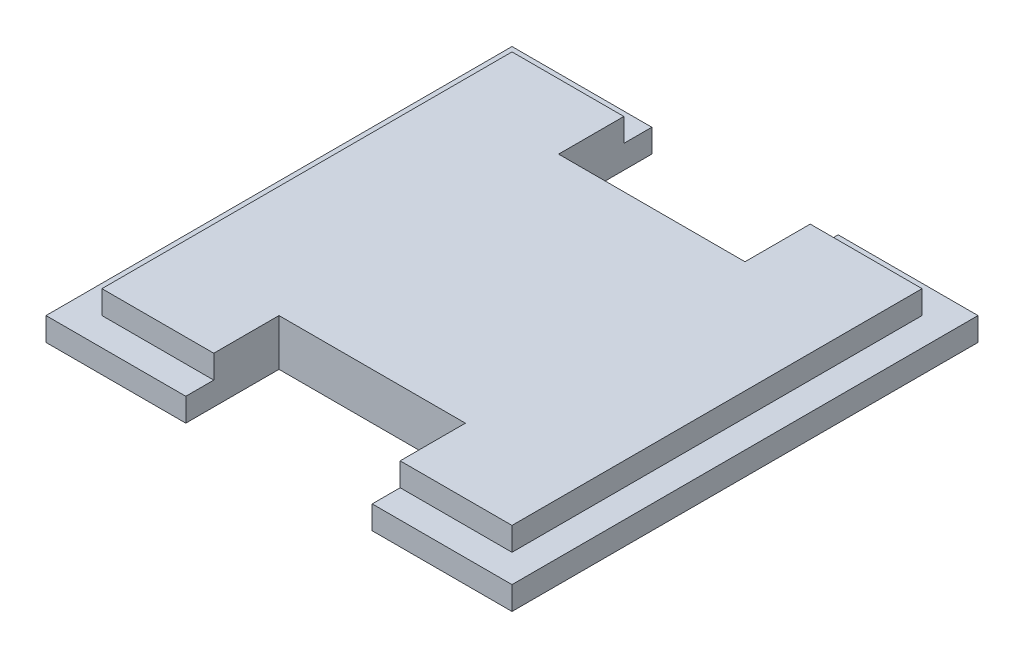
SolidWorks part; units mm, degrees
ref_plane "Front Plane" through (0, 0, 0) normal (0, 0, 1) x (1, 0, 0)
ref_plane "Top Plane" through (0, 0, 0) normal (0, 1, 0) x (1, 0, 0)
ref_plane "Right Plane" through (0, 0, 0) normal (1, 0, 0) x (0, 0, -1)
sketch "Sketch1" plane through (0, 0, 0) normal (0, 1, 0) x (1, 0, 0)
  line L1 (0, 0) -> (100, 0)
  line L2 (0, 0) -> (0, 100)
  line L3 (0, 100) -> (100, 100)
  line L4 (100, 0) -> (100, 100)
  dimension "D1" = 100
  dimension "D2" = 100
extrude "Boss-Extrude1" add sketch "Sketch1" along normal blind 5
sketch "Sketch2" plane through (0, 5, 0) normal (0, 1, 0) x (1, 0, 0)
  line L8 (94, 6) -> (94, 94)
  line L9 (6, 6) -> (94, 6)
  line L10 (6, 94) -> (6, 6)
  line L11 (94, 94) -> (6, 94)
  line L12 (94, 6) -> (94, 94)
  line L13 (6, 6) -> (94, 6)
  line L14 (6, 94) -> (6, 6)
  line L15 (94, 94) -> (6, 94)
  dimension "D1" = 6
extrude "Boss-Extrude2" add sketch "Sketch2" along normal blind 5
sketch "Sketch3" plane through (0, 0, 0) normal (0, -1, 0) x (1, 0, 0)
  line L0 (100, -100) -> (0, -100) construction
  line L1 (30, -100) -> (70, -100)
  line L2 (30, -100) -> (30, -80)
  line L3 (30, -80) -> (70, -80)
  line L4 (70, -100) -> (70, -80)
  line L6 (50, 0) -> (50, -100) construction
  line L7 (0, 0) -> (100, 0) construction
  line L19 (0, -50) -> (100, -50) construction
  line L20 (0, -100) -> (0, 0) construction
  line L21 (100, 0) -> (100, -100) construction
  line L22 (30, -20) -> (70, -20)
  line L23 (70, 0) -> (70, -20)
  line L24 (30, 0) -> (70, 0)
  line L25 (30, 0) -> (30, -20)
  point P10 (50, -80)
  point P11 (50, -50)
  dimension "D1" = 20
  dimension "D2" = 40
extrude "Cut-Extrude1" cut sketch "Sketch3" against normal blind 10
